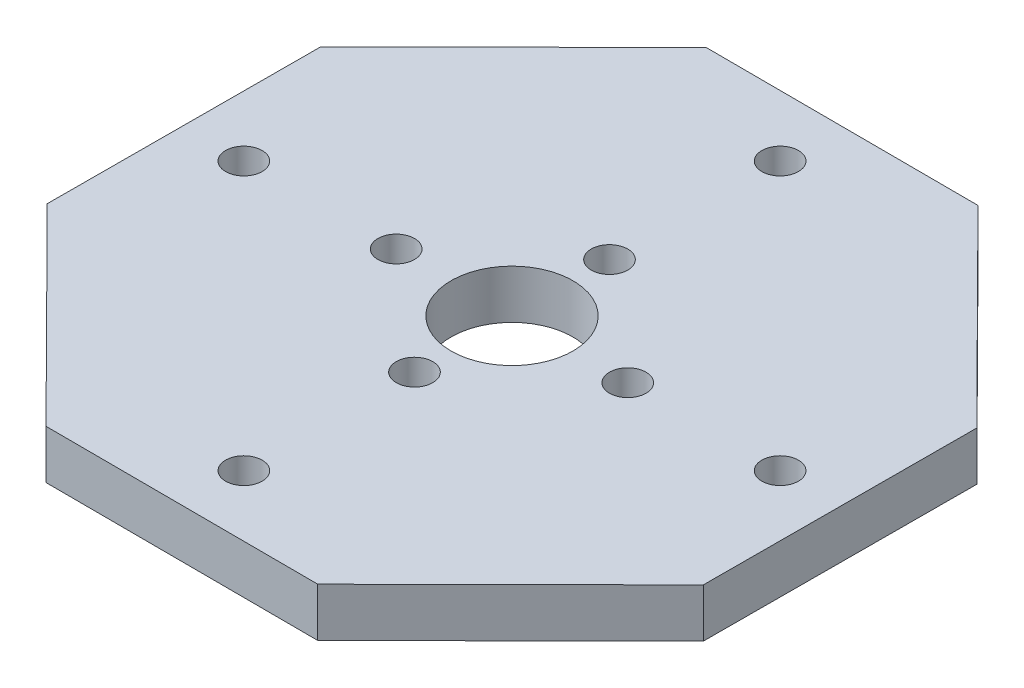
SolidWorks part; units mm, degrees
material "ABS PC"
ref_plane "Front Plane" through (0, 0, 0) normal (0, 0, 1) x (1, 0, 0)
ref_plane "Top Plane" through (0, 0, 0) normal (0, 1, 0) x (1, 0, 0)
ref_plane "Right Plane" through (0, 0, 0) normal (1, 0, 0) x (0, 0, -1)
sketch "Sketch1" plane through (0, 0, 0) normal (0, 1, 0) x (1, 0, 0)
  line L0 (-9.5, 0) -> (9.5, 0) construction
  line L1 (11.2705, 26.9639) -> (-11.0969, 27.0358)
  line L2 (-11.0969, 27.0358) -> (-26.9639, 11.2705)
  line L3 (-26.9639, 11.2705) -> (-27.0358, -11.0969)
  line L4 (-27.0358, -11.0969) -> (-11.2705, -26.9639)
  line L5 (-11.2705, -26.9639) -> (11.0969, -27.0358)
  line L6 (11.0969, -27.0358) -> (26.9639, -11.2705)
  line L7 (26.9639, -11.2705) -> (27.0358, 11.0969)
  line L8 (27.0358, 11.0969) -> (11.2705, 26.9639)
  line L9 (0, -8) -> (0, 8) construction
  circle A0 centre (0, 0) radius 22 construction
  circle A1 centre (0, 0) radius 27 construction
  circle A2 centre (0, 22) radius 1.5
  circle A3 centre (22, 0) radius 1.5
  circle A4 centre (0, -22) radius 1.5
  circle A5 centre (-22, 0) radius 1.5
  circle A6 centre (0, 0) radius 5
  circle A7 centre (-9.5, 0) radius 1.5
  circle A8 centre (0, -8) radius 1.5
  circle A9 centre (9.5, 0) radius 1.5
  circle A10 centre (0, 8) radius 1.5
  point P24 (0, 0)
  point P25 (0, 0)
  point P27 (0, 0)
  point P29 (0, 0)
  dimension "D1" = 44
  dimension "D2" = 3
  dimension "D4" = 10
  dimension "D6" = 16
  dimension "D7" = 3
  dimension "D8" = 3
  dimension "D9" = 3
  dimension "D10" = 3
  dimension "D5" = 19
  dimension "D3" = 4
extrude "Boss-Extrude1" add sketch "Sketch1" along normal mid plane 4
